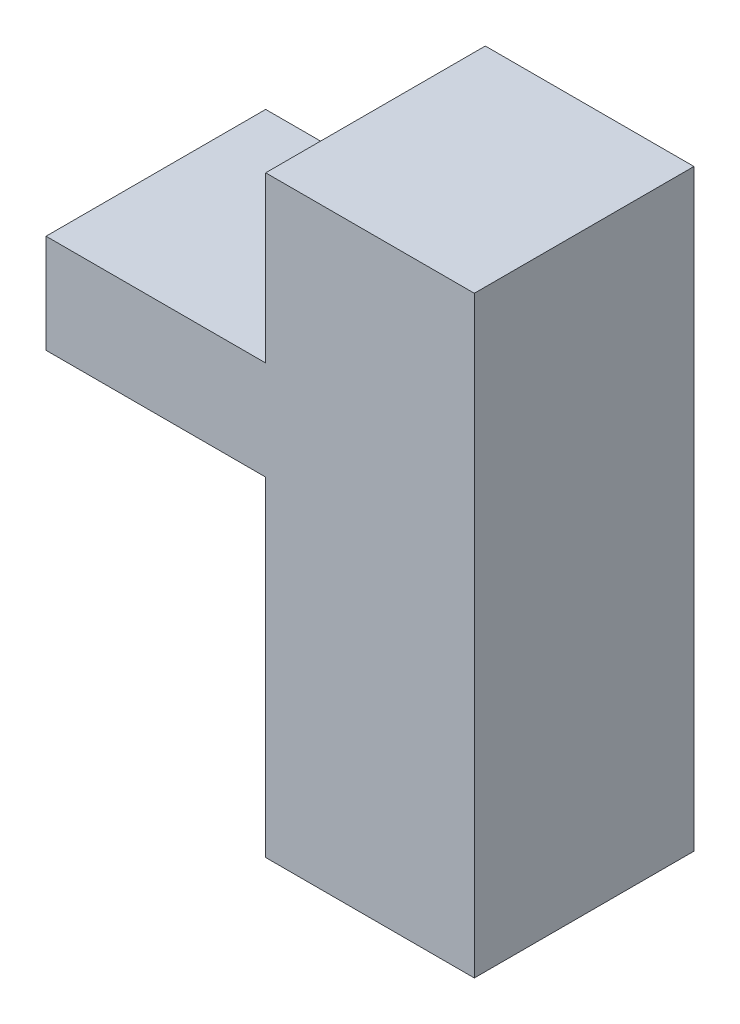
SolidWorks part; units mm, degrees
ref_plane "Front Plane" through (0, 0, 0) normal (0, 0, 1) x (1, 0, 0)
ref_plane "Top Plane" through (0, 0, 0) normal (0, 1, 0) x (1, 0, 0)
ref_plane "Right Plane" through (0, 0, 0) normal (1, 0, 0) x (0, 0, -1)
sketch "Sketch1" plane through (0, 0, 0) normal (0, 0, 1) x (1, 0, 0)
  line L0 (0, 16) -> (0, 22) construction
  line L1 (0, 0) -> (8, 0) construction
  line L2 (0, 0) -> (0, 12) construction
  line L3 (0, 22) -> (8, 22) construction
  line L4 (8, 0) -> (8, 22) construction
  line L5 (0, 16) -> (-8, 16) construction
  line L7 (0, 12) -> (-8, 12) construction
  line L8 (-8, 16) -> (-8, 12) construction
  line L9 (0.2, 0.2) -> (7.8, 0.2)
  line L10 (7.8, 0.2) -> (7.8, 21.8)
  line L11 (0.2, 21.8) -> (7.8, 21.8)
  line L12 (0.2, 15.8) -> (0.2, 21.8)
  line L13 (0.2, 15.8) -> (-7.8, 15.8)
  line L14 (-7.8, 15.8) -> (-7.8, 12.2)
  line L15 (0.2, 12.2) -> (-7.8, 12.2)
  line L16 (0.2, 0.2) -> (0.2, 12.2)
  point P9 (0, 0)
  dimension "D1" = 22
  dimension "D2" = 6
  dimension "D3" = 8
  dimension "D4" = 8
  dimension "D5" = 4
  dimension "D6" = 0.2
extrude "Boss-Extrude1" add sketch "Sketch1" along normal blind 8
